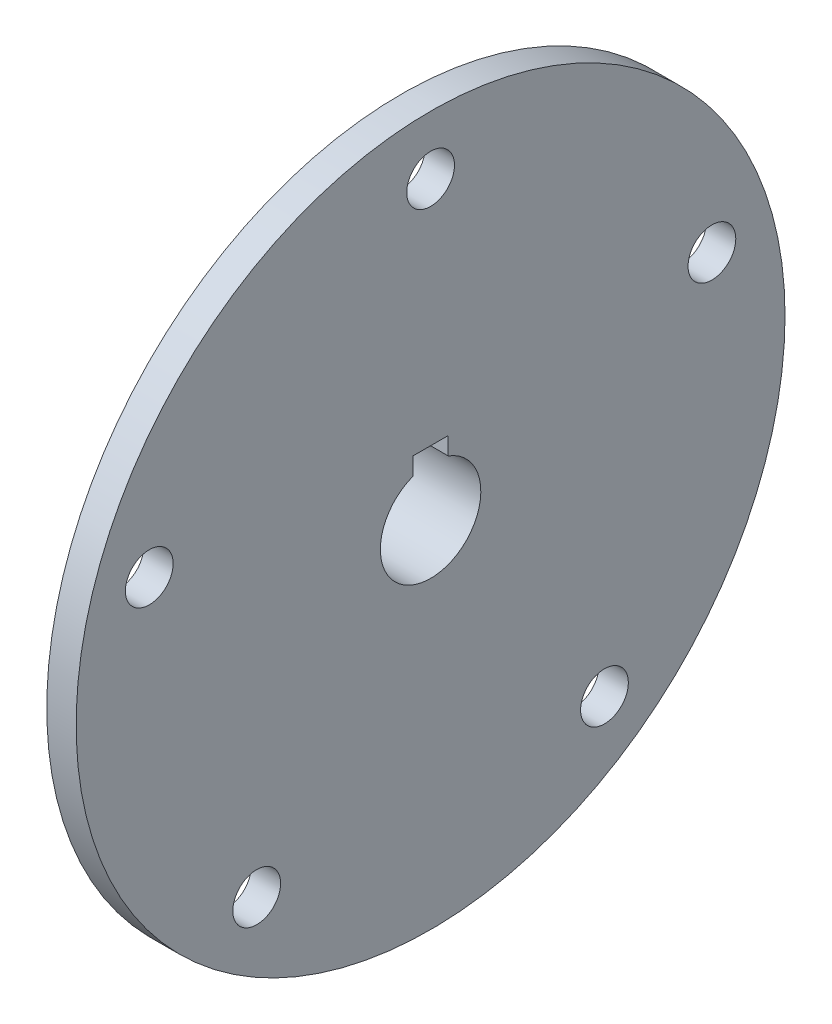
SolidWorks part; units mm, degrees
material "Alloy Steel"
ref_plane "Front Plane" through (0, 0, 0) normal (0, 0, 1) x (1, 0, 0)
ref_plane "Top Plane" through (0, 0, 0) normal (0, 1, 0) x (1, 0, 0)
ref_plane "Right Plane" through (0, 0, 0) normal (1, 0, 0) x (0, 0, -1)
sketch "Sketch1" plane through (0, 0, 0) normal (1, 0, 0) x (0, 0, -1)
  circle A0 centre (0, 0) radius 60.325
  dimension "D1" = 120.65
extrude "Boss-Extrude1" add sketch "Sketch1" against normal blind 5
sketch "Sketch2" plane through (0, 0, 0) normal (1, 0, 0) x (0, 0, -1)
  line L0 (0, 60.325) -> (0, -60.325) construction
  circle A1 centre (0, 0) radius 60.325 construction
  circle A16 centre (0, 50.343) radius 4.064
  circle A17 centre (47.879, 15.5568) radius 4.064
  circle A18 centre (29.5908, -40.7283) radius 4.064
  circle A19 centre (-29.5908, -40.7283) radius 4.064
  circle A20 centre (-47.879, 15.5568) radius 4.064
extrude "Cut-Extrude1" cut sketch "Sketch2" against normal through all
sketch "Sketch11" plane through (-5, 0, 0) normal (-1, 0, 0) x (0, 0, 1)
  circle A0 centre (0, 0) radius 17.5
  dimension "D1" = 35
extrude "Boss-Extrude3" add sketch "Sketch11" along normal blind 30
sketch "Sketch12" plane through (-35, 0, 0) normal (-1, 0, 0) x (0, 0, 1)
  line L0 (0, 5.55) -> (0, 8.55) construction
  line L1 (0, 8.55) -> (0, 11.0064) construction
  line L2 (0, 11.0064) -> (-3, 11.0064)
  line L3 (-3, 11.0064) -> (-3, 8.0064)
  line L4 (0, 11.0064) -> (3, 11.0064)
  line L5 (3, 11.0064) -> (3, 8.0064)
  line L6 (-3, 8.0064) -> (3, 8.0064) construction
  arc A0 (-3, 8.0064) -> (3, 8.0064) centre (0, 0) ccw
  dimension "D1" = 17.1
  dimension "D2" = 3
  dimension "D3" = 3
extrude "Cut-Extrude5" cut sketch "Sketch12" against normal through all
ref_plane "Plane_MotorSideFace" through (-35, 0, 0) normal (1, 0, 0) x (0, 0, -1)
sketch "Sketch13" plane through (-35, 0, 0) normal (1, 0, 0) x (0, 0, -1)
  circle A0 centre (0, 0) radius 11
extrude "Cut_MotorShoulderRecess_D22x3" cut sketch "Sketch13" along normal blind 3
